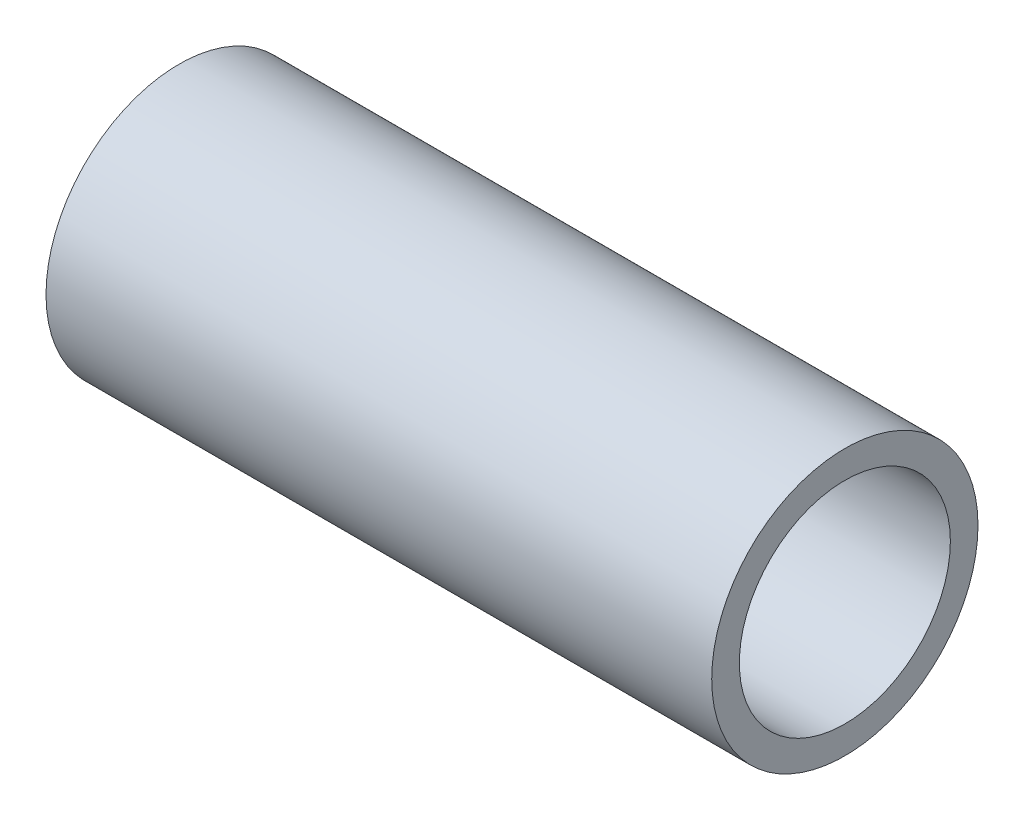
SolidWorks part; units mm, degrees
ref_plane "Front Plane" through (0, 0, 0) normal (0, 0, 1) x (1, 0, 0)
ref_plane "Top Plane" through (0, 0, 0) normal (0, 1, 0) x (1, 0, 0)
ref_plane "Right Plane" through (0, 0, 0) normal (1, 0, 0) x (0, 0, -1)
sketch "Sketch1" plane through (0, 0, 0) normal (1, 0, 0) x (0, 0, -1)
  circle A0 centre (0, 0) radius 4
extrude "Boss-Extrude1" add sketch "Sketch1" along normal blind 20
sketch "Sketch2" plane through (20, 0, 0) normal (1, 0, 0) x (0, 0, -1)
  circle A0 centre (0, 0) radius 3.1699
  dimension "D1" = 6.3398
extrude "Cut-Extrude1" cut sketch "Sketch2" against normal blind 6.35
